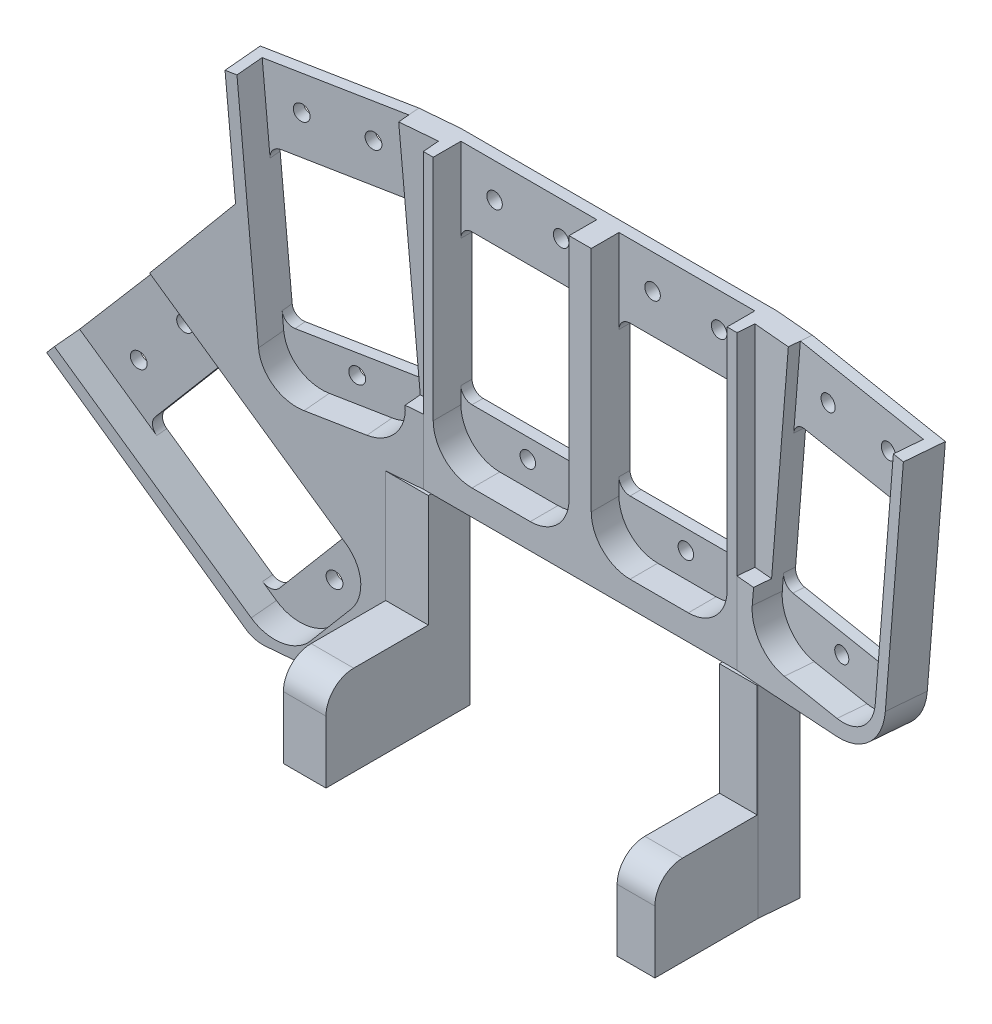
SolidWorks part; units mm, degrees
ref_plane "前视基准面" through (0, 0, 0) normal (0, 0, 1) x (1, 0, 0)
ref_plane "上视基准面" through (0, 0, 0) normal (0, 1, 0) x (1, 0, 0)
ref_plane "右视基准面" through (0, 0, 0) normal (1, 0, 0) x (0, 0, -1)
other "Configuration Table"
sketch "草图1" plane through (0, 0, 0) normal (0, 0, 1) x (1, 0, 0)
  line L0 (-6.3171, -14.436) -> (-6.3171, -11.436)
  line L1 (-8.3171, -13.436) -> (-28.8171, -13.436)
  line L2 (-30.8171, -11.436) -> (-30.8171, -14.436)
  line L3 (-23.8171, -21.436) -> (-13.3171, -21.436)
  line L4 (22.1829, -14.436) -> (22.1829, -11.436)
  line L5 (20.1829, -13.436) -> (-0.3171, -13.436)
  line L6 (-2.3171, -11.436) -> (-2.3171, -14.436)
  line L7 (4.6829, -21.436) -> (15.1829, -21.436)
  line L8 (22.1829, 11.564) -> (22.1829, 26.7199)
  line L9 (22.1829, 26.7199) -> (-2.3171, 26.7199)
  line L10 (-2.3171, 26.7199) -> (-2.3171, 11.564)
  line L11 (-0.3171, 13.564) -> (20.1829, 13.564)
  line L12 (-6.3171, 11.564) -> (-6.3171, 26.7199)
  line L13 (-6.3171, 26.7199) -> (-30.8171, 26.7199)
  line L14 (-30.8171, 26.7199) -> (-30.8171, 11.564)
  line L15 (-28.8171, 13.564) -> (-8.3171, 13.564)
  line L16 (-30.8171, 11.564) -> (-30.8171, -11.436)
  line L17 (-6.3171, 11.564) -> (-6.3171, -11.436)
  line L18 (22.1829, 11.564) -> (22.1829, -11.436)
  line L19 (-2.3171, 11.564) -> (-2.3171, -11.436)
  line L20 (-6.3171, 26.7199) -> (-2.3171, 26.7199)
  line L21 (-30.8171, 26.7199) -> (-32.8171, 26.7199)
  line L22 (-32.8171, 26.7199) -> (-32.8171, -25.4093)
  line L23 (-32.8171, -25.4093) -> (24.1829, -25.4093)
  line L24 (22.1829, 26.7199) -> (24.1829, 26.7199)
  line L25 (24.1829, 26.7199) -> (24.1829, -25.4093)
  arc A0 (-13.3171, -21.436) -> (-6.3171, -14.436) centre (-13.3171, -14.436) ccw
  arc A1 (-8.3171, -13.436) -> (-6.3171, -11.436) centre (-8.3171, -11.436) ccw
  arc A2 (-30.8171, -11.436) -> (-28.8171, -13.436) centre (-28.8171, -11.436) ccw
  arc A3 (-30.8171, -14.436) -> (-23.8171, -21.436) centre (-23.8171, -14.436) ccw
  arc A4 (15.1829, -21.436) -> (22.1829, -14.436) centre (15.1829, -14.436) ccw
  arc A5 (20.1829, -13.436) -> (22.1829, -11.436) centre (20.1829, -11.436) ccw
  arc A6 (-2.3171, -11.436) -> (-0.3171, -13.436) centre (-0.3171, -11.436) ccw
  arc A7 (-2.3171, -14.436) -> (4.6829, -21.436) centre (4.6829, -14.436) ccw
  arc A8 (-0.3171, 13.564) -> (-2.3171, 11.564) centre (-0.3171, 11.564) ccw
  arc A9 (22.1829, 11.564) -> (20.1829, 13.564) centre (20.1829, 11.564) ccw
  arc A10 (-28.8171, 13.564) -> (-30.8171, 11.564) centre (-28.8171, 11.564) ccw
  arc A11 (-6.3171, 11.564) -> (-8.3171, 13.564) centre (-8.3171, 11.564) ccw
sketch "草图2" plane through (0, 0, 0) normal (0, 0, 1) x (1, 0, 0)
  line L0 (-6.3171, -14.436) -> (-6.3171, -11.436)
  line L1 (-8.3171, -13.436) -> (-28.8171, -13.436)
  line L2 (-30.8171, -11.436) -> (-30.8171, -14.436)
  line L3 (-23.8171, -21.436) -> (-13.3171, -21.436)
  line L4 (22.1829, -14.436) -> (22.1829, -11.436)
  line L5 (20.1829, -13.436) -> (-0.3171, -13.436)
  line L6 (-2.3171, -11.436) -> (-2.3171, -14.436)
  line L7 (4.6829, -21.436) -> (15.1829, -21.436)
  line L8 (22.1829, 11.564) -> (22.1829, 26.7199)
  line L9 (22.1829, 26.7199) -> (-2.3171, 26.7199)
  line L10 (-2.3171, 26.7199) -> (-2.3171, 11.564)
  line L11 (-0.3171, 13.564) -> (20.1829, 13.564)
  line L12 (-6.3171, 11.564) -> (-6.3171, 26.7199)
  line L13 (-6.3171, 26.7199) -> (-30.8171, 26.7199)
  line L14 (-30.8171, 26.7199) -> (-30.8171, 11.564)
  line L15 (-28.8171, 13.564) -> (-8.3171, 13.564)
  line L16 (-30.8171, 11.564) -> (-30.8171, -11.436)
  line L17 (-6.3171, 11.564) -> (-6.3171, -11.436)
  line L18 (22.1829, 11.564) -> (22.1829, -11.436)
  line L19 (-2.3171, 11.564) -> (-2.3171, -11.436)
  line L20 (-6.3171, 26.7199) -> (-2.3171, 26.7199)
  line L21 (-30.8171, 26.7199) -> (-32.8171, 26.7199)
  line L22 (-32.8171, 26.7199) -> (-32.8171, -25.4093)
  line L23 (-32.8171, -25.4093) -> (24.1829, -25.4093)
  line L24 (22.1829, 26.7199) -> (24.1829, 26.7199)
  line L25 (24.1829, 26.7199) -> (24.1829, -25.4093)
  arc A0 (-13.3171, -21.436) -> (-6.3171, -14.436) centre (-13.3171, -14.436) ccw
  arc A1 (-8.3171, -13.436) -> (-6.3171, -11.436) centre (-8.3171, -11.436) ccw
  arc A2 (-30.8171, -11.436) -> (-28.8171, -13.436) centre (-28.8171, -11.436) ccw
  arc A3 (-30.8171, -14.436) -> (-23.8171, -21.436) centre (-23.8171, -14.436) ccw
  arc A4 (15.1829, -21.436) -> (22.1829, -14.436) centre (15.1829, -14.436) ccw
  arc A5 (20.1829, -13.436) -> (22.1829, -11.436) centre (20.1829, -11.436) ccw
  arc A6 (-2.3171, -11.436) -> (-0.3171, -13.436) centre (-0.3171, -11.436) ccw
  arc A7 (-2.3171, -14.436) -> (4.6829, -21.436) centre (4.6829, -14.436) ccw
  arc A8 (-0.3171, 13.564) -> (-2.3171, 11.564) centre (-0.3171, 11.564) ccw
  arc A9 (22.1829, 11.564) -> (20.1829, 13.564) centre (20.1829, 11.564) ccw
  arc A10 (-28.8171, 13.564) -> (-30.8171, 11.564) centre (-28.8171, 11.564) ccw
  arc A11 (-6.3171, 11.564) -> (-8.3171, 13.564) centre (-8.3171, 11.564) ccw
extrude "凸台-拉伸3" add sketch "草图1" along normal blind 2 contours A11 L12 L13 L14 A10 L15 | A9 L8 L9 L10 A8 L11 | L6 A7 L7 A4 L4 A5 L5 A6 | L2 A3 L3 A0 L0 A1 L1 A2 | A7 L6 L19 L10 L20 L12 L17 L0 A0 L3 A3 L2 L16 L14 L21 L22 L23 L25 L24 L8 L18 L4 A4 L7
sketch "草图4" plane through (0, 0, 2) normal (0, 0, 1) x (1, 0, 0)
  line L0 (4.6829, -21.436) -> (15.1829, -21.436) construction
  line L1 (22.1829, -14.436) -> (22.1829, -11.436) construction
  line L2 (22.1829, 11.564) -> (22.1829, -11.436) construction
  line L3 (22.1829, 26.7199) -> (24.1829, 26.7199) construction
  line L4 (24.1829, 26.7199) -> (24.1829, -25.4093) construction
  line L5 (22.1829, 11.564) -> (22.1829, 26.7199) construction
  line L6 (-2.3171, 26.7199) -> (-2.3171, 11.564) construction
  line L7 (-2.3171, 11.564) -> (-2.3171, -11.436) construction
  line L8 (-2.3171, -11.436) -> (-2.3171, -14.436) construction
  line L9 (-32.8171, -25.4093) -> (24.1829, -25.4093) construction
  line L10 (-32.8171, 26.7199) -> (-32.8171, -25.4093) construction
  line L11 (-30.8171, 26.7199) -> (-32.8171, 26.7199) construction
  line L12 (-6.3171, 11.564) -> (-6.3171, 26.7199) construction
  line L13 (-6.3171, 11.564) -> (-6.3171, -11.436) construction
  line L14 (-6.3171, -14.436) -> (-6.3171, -11.436) construction
  line L15 (-23.8171, -21.436) -> (-13.3171, -21.436) construction
  line L16 (-30.8171, -11.436) -> (-30.8171, -14.436) construction
  line L17 (-30.8171, 11.564) -> (-30.8171, -11.436) construction
  line L18 (-30.8171, 26.7199) -> (-30.8171, 11.564) construction
  line L19 (4.6829, -21.436) -> (15.1829, -21.436)
  line L20 (22.1829, -14.436) -> (22.1829, -11.436)
  line L21 (22.1829, 11.564) -> (22.1829, -11.436)
  line L22 (22.1829, 26.7199) -> (24.1829, 26.7199)
  line L23 (24.1829, 26.7199) -> (24.1829, -25.4093)
  line L24 (22.1829, 11.564) -> (22.1829, 26.7199)
  line L25 (-2.3171, 26.7199) -> (-2.3171, 11.564)
  line L26 (-2.3171, 11.564) -> (-2.3171, -11.436)
  line L27 (-2.3171, -11.436) -> (-2.3171, -14.436)
  line L28 (-32.8171, -25.4093) -> (24.1829, -25.4093)
  line L29 (-32.8171, 26.7199) -> (-32.8171, -25.4093)
  line L30 (-30.8171, 26.7199) -> (-32.8171, 26.7199)
  line L31 (-6.3171, 11.564) -> (-6.3171, 26.7199)
  line L32 (-6.3171, 11.564) -> (-6.3171, -11.436)
  line L33 (-6.3171, -14.436) -> (-6.3171, -11.436)
  line L34 (-23.8171, -21.436) -> (-13.3171, -21.436)
  line L35 (-30.8171, -11.436) -> (-30.8171, -14.436)
  line L36 (-30.8171, 11.564) -> (-30.8171, -11.436)
  line L37 (-30.8171, 26.7199) -> (-30.8171, 11.564)
  line L38 (-6.3171, 26.7199) -> (-2.3171, 26.7199)
  arc A0 (15.1829, -21.436) -> (22.1829, -14.436) centre (15.1829, -14.436) ccw construction
  arc A1 (-2.3171, -14.436) -> (4.6829, -21.436) centre (4.6829, -14.436) ccw construction
  arc A2 (-13.3171, -21.436) -> (-6.3171, -14.436) centre (-13.3171, -14.436) ccw construction
  arc A3 (-30.8171, -14.436) -> (-23.8171, -21.436) centre (-23.8171, -14.436) ccw construction
  arc A4 (15.1829, -21.436) -> (22.1829, -14.436) centre (15.1829, -14.436) ccw
  arc A5 (-2.3171, -14.436) -> (4.6829, -21.436) centre (4.6829, -14.436) ccw
  arc A6 (-13.3171, -21.436) -> (-6.3171, -14.436) centre (-13.3171, -14.436) ccw
  arc A7 (-30.8171, -14.436) -> (-23.8171, -21.436) centre (-23.8171, -14.436) ccw
extrude "凸台-拉伸4" add sketch "草图4" along normal blind 5
sketch "草图5" plane through (0, 0, 2) normal (0, 0, 1) x (1, 0, 0)
  circle A0 centre (9.747, -16.936) radius 1.4
  circle A5 centre (-18.753, -16.936) radius 1.4
  circle A10 centre (-24.753, 20.564) radius 1.4
  circle A11 centre (-12.753, 20.564) radius 1.4
  circle A13 centre (3.747, 20.564) radius 1.4
  circle A14 centre (15.747, 20.564) radius 1.4
extrude "切除-拉伸1" cut sketch "草图5" against normal blind 5
sketch "草图7" plane through (0, 26.7199, 0) normal (0, 1, 0) x (1, 0, 0)
  line L0 (-32.8171, 0) -> (-70.2267, -3.2729)
  line L1 (-32.8171, -7) -> (-32.8171, 0) construction
  line L2 (-32.8171, 0) -> (-32.8171, -2)
  line L3 (-32.8171, -2) -> (-70.053, -5.2577)
  line L4 (-70.2267, -3.2729) -> (-70.053, -5.2577)
  dimension "D1" = 85
extrude "凸台-拉伸5" add sketch "草图7" against normal up to surface (52.1292 mm away) up to face at (-4.3171, -25.4093, 3.5)
sketch "草图8" plane through (-0.0756, 0, -0.8645) normal (0.0872, 0, 0.9962) x (0.9962, 0, -0.0872)
  line L0 (-36.1156, -14.2794) -> (-36.3771, -11.2908)
  line L2 (-60.7838, -13.4261) -> (-60.5224, -16.4147)
  line L4 (-38.3817, 11.6217) -> (-39.7026, 26.7199)
  line L5 (-39.7026, 26.7199) -> (-64.1093, 24.5846)
  line L6 (-64.1093, 24.5846) -> (-62.7884, 9.4864)
  line L8 (-62.7884, 9.4864) -> (-60.7838, -13.4261)
  line L9 (-38.3817, 11.6217) -> (-36.3771, -11.2908)
  line L10 (-70.2447, 26.7199) -> (-32.8666, 26.7199) construction
  line L11 (-36.1156, -14.2794) -> (-36.3771, -11.2908)
  line L12 (-38.1951, -13.4575) -> (-58.6171, -15.2442)
  line L13 (-52.9389, -22.7779) -> (-42.4789, -21.8628)
  line L14 (-60.9703, 11.6531) -> (-40.5484, 13.4398)
  line L15 (-38.3817, 11.6217) -> (-39.7026, 26.7199)
  arc A1 (-38.1951, -13.4575) -> (-36.3771, -11.2908) centre (-38.3695, -11.4651) ccw
  arc A2 (-60.7838, -13.4261) -> (-58.6171, -15.2442) centre (-58.7915, -13.2518) ccw
  arc A3 (-60.5224, -16.4147) -> (-52.9389, -22.7779) centre (-53.549, -15.8046) ccw
  arc A4 (-60.9703, 11.6531) -> (-62.7884, 9.4864) centre (-60.796, 9.6607) ccw
  arc A5 (-38.3817, 11.6217) -> (-40.5484, 13.4398) centre (-40.374, 11.4474) ccw
  circle A6 centre (-48.2863, -17.8537) radius 1.4
  arc A7 (-38.1951, -13.4575) -> (-36.3771, -11.2908) centre (-38.3695, -11.4651) ccw
  arc A8 (-42.4789, -21.8628) -> (-36.1156, -14.2794) centre (-43.089, -14.8894) ccw
  circle A9 centre (-57.5318, 18.9807) radius 1.4
  circle A10 centre (-45.5775, 20.0265) radius 1.4
  arc A11 (-38.3817, 11.6217) -> (-40.5484, 13.4398) centre (-40.374, 11.4474) ccw
extrude "切除-拉伸2" cut sketch "草图8" against normal blind 54 contours A9 | A10 | A6 | L9 A5 L14 A4 L8 A2 L12 A1
sketch "草图9" plane through (-0.0756, 0, -0.8645) normal (0.0872, 0, 0.9962) x (0.9962, 0, -0.0872)
  line L0 (-38.3817, 11.6217) -> (-39.7026, 26.7199)
  line L1 (-70.2447, 26.7199) -> (-32.8666, 26.7199) construction
  line L2 (-39.7026, 26.7199) -> (-32.8666, 26.7199)
  line L3 (-32.8666, 26.7199) -> (-32.8666, -25.4093)
  line L4 (-32.8666, -25.4093) -> (-61.7354, -25.4093)
  line L5 (-60.7838, -13.4261) -> (-60.5224, -16.4147)
  line L6 (-60.7838, -13.4261) -> (-62.7884, 9.4864)
  line L7 (-62.7884, 9.4864) -> (-64.2962, 26.7199)
  line L8 (-64.2962, 26.7199) -> (-66.2962, 26.7199)
  line L9 (-66.2962, 26.7199) -> (-61.7354, -25.4093)
  line L10 (-60.7838, -13.4261) -> (-60.5224, -16.4147)
  line L11 (-36.1156, -14.2794) -> (-36.3771, -11.2908)
  line L13 (-52.9389, -22.7779) -> (-42.4789, -21.8628)
  line L14 (-38.3817, 11.6217) -> (-36.3771, -11.2908)
  circle A0 centre (-48.2863, -17.8537) radius 1.4
  arc A2 (-60.5224, -16.4147) -> (-52.9389, -22.7779) centre (-53.549, -15.8046) ccw
  arc A4 (-42.4789, -21.8628) -> (-36.1156, -14.2794) centre (-43.089, -14.8894) ccw
  line M17 (-70.2447, -25.4093) -> (-32.8666, -25.4093)
  line M18 (-32.8666, -25.4093) -> (-32.8666, 26.7199)
  line M19 (-32.8666, 26.7199) -> (-70.2447, 26.7199)
  line M22 (-38.3817, 11.6217) -> (-36.3771, -11.2908)
  line M26 (-60.7838, -13.4261) -> (-62.7884, 9.4864)
extrude "凸台-拉伸6" add sketch "草图9" along normal blind 5 contours A4 L13 A2 L5 L7 L9 L0 L11 M26 M19 M17 M18 M22
sketch "草图10" plane through (0, 26.7199, 0) normal (0, 1, 0) x (1, 0, 0)
  line L0 (24.1829, 0) -> (76.1307, -4.5448)
  line L1 (24.1829, -7) -> (24.1829, 0) construction
  line L3 (24.1829, -2) -> (76.1722, -6.5485)
  line L4 (76.1307, -4.5448) -> (76.1722, -6.5485)
  line L5 (24.1829, 0) -> (24.1829, -2)
  dimension "D1" = 85
extrude "凸台-拉伸7" add sketch "草图10" against normal up to surface (52.1292 mm away) up to face at (-35.0058, -25.4093, 4.568)
sketch "草图11" plane through (0.01, 0, -0.1148) normal (-0.0872, 0, 0.9962) x (0.9962, 0, 0.0872)
  line L0 (29.7802, 11.6217) -> (27.7757, -11.2908)
  line L1 (44.3375, -22.7779) -> (33.8775, -21.8628)
  line L2 (27.5142, -14.2794) -> (27.7757, -11.2908)
  line L3 (52.1824, -13.4261) -> (51.921, -16.4147)
  line L4 (57.6948, 26.7199) -> (53.134, -25.4093)
  line L5 (55.6948, 26.7199) -> (57.6948, 26.7199)
  line L6 (54.187, 9.4864) -> (55.6948, 26.7199)
  line L7 (52.1824, -13.4261) -> (54.187, 9.4864)
  line L8 (52.1824, -13.4261) -> (51.921, -16.4147)
  line L9 (24.2652, -25.4093) -> (53.134, -25.4093)
  line L10 (24.2652, 26.7199) -> (24.2652, -25.4093)
  line L11 (31.1012, 26.7199) -> (24.2652, 26.7199)
  line L12 (29.7802, 11.6217) -> (31.1012, 26.7199)
  arc A0 (33.8775, -21.8628) -> (27.5142, -14.2794) centre (34.4876, -14.8894) cw
  arc A1 (51.921, -16.4147) -> (44.3375, -22.7779) centre (44.9476, -15.8046) cw
  circle A2 centre (39.6849, -17.8537) radius 1.4
  line M1 (24.2652, -25.4093) -> (76.4531, -25.4093)
  line M3 (76.4531, 26.7199) -> (24.2652, 26.7199)
  line M4 (24.2652, 26.7199) -> (24.2652, -25.4093)
extrude "凸台-拉伸8" add sketch "草图11" along normal blind 5 contours L3 A1 L1 A0 L2 L0 L12 L4 L6 L7 M3 M4 M1
sketch "草图12" plane through (0.01, 0, -0.1148) normal (-0.0872, 0, 0.9962) x (0.9962, 0, 0.0872)
  line L6 (50.0157, -15.2442) -> (29.5937, -13.4575)
  line L8 (31.9469, 13.4398) -> (52.3689, 11.6531)
  line L9 (29.7802, 11.6217) -> (27.7757, -11.2908)
  line L10 (54.187, 9.4864) -> (52.1824, -13.4261)
  circle A5 centre (36.6057, 20.0589) radius 1.4
  circle A6 centre (48.56, 19.0131) radius 1.4
  circle A7 centre (39.3145, -17.8213) radius 1.4
  arc A8 (27.7757, -11.2908) -> (29.5937, -13.4575) centre (29.768, -11.4651) ccw
  arc A10 (50.0157, -15.2442) -> (52.1824, -13.4261) centre (50.19, -13.2518) ccw
  arc A12 (54.187, 9.4864) -> (52.3689, 11.6531) centre (52.1946, 9.6607) ccw
  arc A13 (31.9469, 13.4398) -> (29.7802, 11.6217) centre (31.7726, 11.4474) ccw
extrude "切除-拉伸3" cut sketch "草图12" against normal blind 5
sketch "草图14" plane through (0, -25.4093, 0) normal (0, -1, 0) x (1, 0, 0)
  line L12 (52.5061, 9.4971) -> (23.9646, 7)
  line L13 (23.9646, 7) -> (-32.5988, 7)
  line L14 (-32.5988, 7) -> (-61.1404, 9.4971)
  line L15 (-61.1404, 9.4971) -> (-61.5762, 4.5161)
  line L16 (-61.5762, 4.5161) -> (-70.053, 5.2577)
  line L17 (-70.053, 5.2577) -> (-70.2267, 3.2729)
  line L18 (-70.2267, 3.2729) -> (-32.8171, 0)
  line L19 (-32.8171, 0) -> (24.1829, 0)
  line L20 (24.1829, 0) -> (76.1307, 4.5448)
  line L21 (76.1307, 4.5448) -> (76.1722, 6.5485)
  line L22 (76.1722, 6.5485) -> (52.9419, 4.5161)
  line L23 (52.9419, 4.5161) -> (52.5061, 9.4971)
  line L24 (52.5061, 9.4971) -> (23.9646, 7)
  line L26 (-32.5988, 7) -> (-61.1404, 9.4971)
  line L27 (-61.1404, 9.4971) -> (-61.5762, 4.5161)
  line L28 (-61.5762, 4.5161) -> (-70.053, 5.2577)
  line L29 (-70.053, 5.2577) -> (-70.2267, 3.2729)
  line L30 (-70.2267, 3.2729) -> (-32.8171, 0)
  line L31 (-32.8171, 0) -> (24.1829, 0)
  line L32 (24.1829, 0) -> (76.1307, 4.5448)
  line L33 (76.1307, 4.5448) -> (76.1722, 6.5485)
  line L34 (76.1722, 6.5485) -> (52.9419, 4.5161)
  line L35 (52.9419, 4.5161) -> (52.5061, 9.4971)
  line L36 (23.9646, 7) -> (-32.5988, 7)
  dimension "D1" = 0
extrude "凸台-拉伸9" add sketch "草图14" along normal blind 48
sketch "草图16" plane through (-69.9774, 0, 6.1222) normal (-0.9962, 0, 0.0872) x (0.0872, 0, 0.9962)
  line L4 (-2.8602, 26.7199) -> (-2.8602, -73.4093)
  line L5 (-2.8602, -73.4093) -> (-0.8678, -73.4093)
  line L6 (-0.8678, -73.4093) -> (-0.8678, 26.7199)
  line L7 (-0.8678, 26.7199) -> (-2.8602, 26.7199)
  line L8 (-2.8602, 26.7199) -> (-2.8602, -73.4093)
  line L9 (-2.8602, -73.4093) -> (-0.8678, -73.4093)
  line L10 (-0.8678, -73.4093) -> (-0.8678, 26.7199)
  line L11 (-0.8678, 26.7199) -> (-2.8602, 26.7199)
  dimension "D1" = 0
extrude "凸台-拉伸10" add sketch "草图16" along normal blind 31
sketch "草图19" plane through (-0.0756, 0, -0.8645) normal (0.0872, 0, 0.9962) x (0.9962, 0, -0.0872)
  line L5 (-66.2962, 26.7199) -> (-101.2447, 26.7199)
  line L6 (-101.2447, 26.7199) -> (-101.2447, -73.4093)
  line L7 (-101.2447, -73.4093) -> (-61.7354, -73.4093)
  line L8 (-61.7354, -73.4093) -> (-61.7354, -25.4093)
  line L9 (-61.7354, -25.4093) -> (-66.2962, 26.7199)
  line L10 (-66.2962, 26.7199) -> (-101.2447, 26.7199)
  line L11 (-101.2447, 26.7199) -> (-101.2447, -73.4093)
  line L12 (-101.2447, -73.4093) -> (-61.7354, -73.4093)
  line L13 (-61.7354, -73.4093) -> (-61.7354, -25.4093)
  line L14 (-61.7354, -25.4093) -> (-66.2962, 26.7199)
  dimension "D1" = 0
extrude "凸台-拉伸12" add sketch "草图19" along normal blind 5 contours L10 L11 L12 L13 L14
sketch "草图20" plane through (0.3601, 0, 4.1165) normal (0.0872, 0, 0.9962) x (0.9962, 0, -0.0872)
  line L0 (-45.9906, -40.369) -> (-48.2888, -38.4406)
  line L1 (-48.0423, -41.2583) -> (-61.2194, -56.9622)
  line L2 (-64.0371, -57.2087) -> (-61.7389, -59.1371)
  line L3 (-51.8771, -58.2743) -> (-45.1278, -50.2308)
  line L4 (-78.6472, -12.9668) -> (-94.4978, -31.6491)
  line L5 (-94.4978, -31.6491) -> (-81.6561, -42.4246)
  line L6 (-81.9026, -39.6069) -> (-68.7255, -23.903)
  line L7 (-65.9078, -23.6565) -> (-78.6472, -12.9668)
  line L8 (-81.6561, -42.4246) -> (-64.0371, -57.2087)
  line L9 (-65.9078, -23.6565) -> (-48.2888, -38.4406)
  arc A0 (-45.1278, -50.2308) -> (-45.9906, -40.369) centre (-50.4902, -45.7313) ccw
  arc A1 (-48.0423, -41.2583) -> (-48.2888, -38.4406) centre (-49.5744, -39.9727) ccw
  arc A2 (-64.0371, -57.2087) -> (-61.2194, -56.9622) centre (-62.7515, -55.6766) ccw
  arc A3 (-61.7389, -59.1371) -> (-51.8771, -58.2743) centre (-57.2394, -53.7747) ccw
  arc A4 (-81.9026, -39.6069) -> (-81.6561, -42.4246) centre (-80.3705, -40.8925) ccw
  arc A5 (-65.9078, -23.6565) -> (-68.7255, -23.903) centre (-67.1934, -25.1886) ccw
  circle A6 centre (-76.9391, -22.8016) radius 1.4
  circle A7 centre (-84.6526, -31.9941) radius 1.4
  circle A8 centre (-52.0692, -51.5024) radius 1.4
extrude "切除-拉伸4" cut sketch "草图20" against normal blind 5 contours L9 A5 L6 A4 L8 A2 L1 A1 | A6 | A7 | A5 L7 L4 L5 A4 L6 A7 A6 | L2 A3 L3 A0 L0 A1 L1 A2 A8 | A8
sketch "草图22" plane through (-0.0756, 0, -0.8645) normal (0.0872, 0, 0.9962) x (0.9962, 0, -0.0872)
  circle A6 centre (-76.9391, -22.8016) radius 1.4
  circle A7 centre (-84.6526, -31.9941) radius 1.4
  circle A8 centre (-52.0692, -51.5024) radius 1.4
extrude "切除-拉伸5" cut sketch "草图22" against normal through all
sketch "草图23" plane through (-0.0756, 0, -0.8645) normal (0.0872, 0, 0.9962) x (0.9962, 0, -0.0872)
  line L1 (-48.0423, -41.2583) -> (-61.2194, -56.9622)
  line L6 (-81.9026, -39.6069) -> (-68.7255, -23.903)
  line L8 (-81.6561, -42.4246) -> (-64.0371, -57.2087)
  line L9 (-65.9078, -23.6565) -> (-48.2888, -38.4406)
  arc A1 (-48.0423, -41.2583) -> (-48.2888, -38.4406) centre (-49.5744, -39.9727) ccw
  arc A2 (-64.0371, -57.2087) -> (-61.2194, -56.9622) centre (-62.7515, -55.6766) ccw
  arc A4 (-81.9026, -39.6069) -> (-81.6561, -42.4246) centre (-80.3705, -40.8925) ccw
  arc A5 (-65.9078, -23.6565) -> (-68.7255, -23.903) centre (-67.1934, -25.1886) ccw
extrude "切除-拉伸6" cut sketch "草图23" against normal through all
sketch "草图24" plane through (0.3601, 0, 4.1165) normal (0.0872, 0, 0.9962) x (0.9962, 0, -0.0872)
  line L0 (-78.6472, -12.9668) -> (-94.4978, -31.6491)
  line L1 (-48.3684, -73.4093) -> (-101.2447, -73.4093)
  line L6 (-64.2962, 26.7199) -> (-101.2447, 26.7199) construction
  line L7 (-66.2962, 26.7199) -> (-64.3389, 4.3484)
  line L8 (-78.6472, -12.9668) -> (-64.3389, 4.3484)
  line L9 (-66.2962, 26.7199) -> (-101.2447, 26.7199)
  line L10 (-101.2447, 26.7199) -> (-101.2447, -73.4093)
  line L11 (-94.4978, -31.6491) -> (-95.7917, -33.1742)
  line L12 (-95.7917, -33.1742) -> (-48.3684, -73.4093)
  line L13 (-33.0849, -73.4093) -> (-101.2447, -73.4093) construction
extrude "切除-拉伸7" cut sketch "草图24" against normal through all
sketch "草图25" plane through (0, 0, 7) normal (0, 0, 1) x (1, 0, 0)
  line L8 (28.1628, -26.0179) -> (21.3541, -26.0179)
  line L9 (21.3541, -26.0179) -> (21.3541, -62.4789)
  line L10 (21.3541, -62.4789) -> (28.1628, -62.4789)
  line L11 (28.1628, -62.4789) -> (28.1628, -26.0179)
  line L12 (-38.8372, -62.4789) -> (-31.1575, -62.4789)
  line L13 (-31.1575, -62.4789) -> (-31.1575, -26.0179)
  line L14 (-31.1575, -26.0179) -> (-38.8372, -26.0179)
  line L15 (-38.8372, -26.0179) -> (-38.8372, -62.4789)
extrude "凸台-拉伸14" add sketch "草图25" along normal blind 19
sketch "草图26" plane through (0, 0, 7) normal (0, 0, 1) x (1, 0, 0)
  line L1 (-38.8372, -62.4789) -> (76.1722, -62.4789)
  line L2 (-38.8372, -62.4789) -> (-38.8372, -73.4093)
  line L3 (-38.8372, -73.4093) -> (76.1722, -73.4093)
  line L4 (76.1722, -62.4789) -> (76.1722, -73.4093)
  line L5 (-38.8372, -62.4789) -> (-63.6236, -62.4789)
  line L6 (-38.8372, -62.4789) -> (-38.8372, -73.4093)
  line L7 (-38.8372, -73.4093) -> (-63.6236, -73.4093)
  line L8 (-63.6236, -62.4789) -> (-63.6236, -73.4093)
  line M24 (-31.1575, -62.4789) -> (-32.5988, -62.4789)
  line M25 (-32.5988, -62.4789) -> (-32.5988, -73.4093)
  line M26 (-32.5988, -73.4093) -> (23.9646, -73.4093)
  line M27 (23.9646, -73.4093) -> (23.9646, -62.4789)
  line M28 (23.9646, -62.4789) -> (21.3541, -62.4789)
extrude "切除-拉伸8" cut sketch "草图26" against normal through all and the other way through all contours L5 L8 L7 L2 | L1 M24 M25 M26 M27 M28 | L4 L1 L3 M27 | L2 L3 L1 M25
sketch "草图27" plane through (-0.4257, 0, 4.8661) normal (-0.0872, 0, 0.9962) x (0.9962, 0, 0.0872)
  line L1 (57.6948, 26.7199) -> (53.134, -25.4093) construction
  line L2 (57.6948, 26.7199) -> (53.134, -25.4093) construction
  line L3 (53.134, -25.4093) -> (28.6978, -26.0179)
  line L4 (28.6978, -26.0179) -> (28.6978, -62.4789)
  line L5 (28.6978, -62.4789) -> (53.134, -62.4789)
  line L7 (53.134, -62.4789) -> (53.134, -25.4093)
extrude "切除-拉伸9" cut sketch "草图27" against normal through all contours L3 L4 L5 L7
sketch "草图28" plane through (0.01, 0, -0.1148) normal (-0.0872, 0, 0.9962) x (0.9962, 0, 0.0872)
  line L5 (53.134, -62.4789) -> (76.4531, -62.4789)
  line L6 (76.4531, -62.4789) -> (76.4531, 26.7199)
  line L7 (76.4531, 26.7199) -> (57.6948, 26.7199)
  line L8 (57.6948, 26.7199) -> (53.134, -25.4093)
  line L11 (76.4531, -62.4789) -> (76.4531, 26.7199)
  line L12 (76.4531, 26.7199) -> (57.6948, 26.7199)
  line L13 (57.6948, 26.7199) -> (53.134, -25.4093)
  line L15 (53.134, -62.4789) -> (76.4531, -62.4789)
  line L17 (53.134, -25.4093) -> (53.134, -62.4789)
  line L18 (53.134, -25.4093) -> (53.134, -62.4789)
  dimension "D1" = 0
extrude "切除-拉伸10" cut sketch "草图28" against normal through all
sketch "草图29" plane through (-0.0756, 0, -0.8645) normal (0.0872, 0, 0.9962) x (0.9962, 0, -0.0872)
  line L0 (-39.7026, 26.7199) -> (-66.0942, 24.411)
  line L1 (-64.3389, 4.3484) -> (-66.2962, 26.7199) construction
  line L2 (-66.0942, 24.411) -> (-66.2962, 26.7199)
  line L3 (-66.2962, 26.7199) -> (-39.7026, 26.7199)
extrude "切除-拉伸11" cut sketch "草图29" against normal through all and the other way through all
sketch "草图31" plane through (0.01, 0, -0.1148) normal (-0.0872, 0, 0.9962) x (0.9962, 0, 0.0872)
  line L0 (31.1012, 26.7199) -> (57.4927, 24.411)
  line L1 (57.6948, 26.7199) -> (53.134, -25.4093) construction
  line L2 (57.4927, 24.411) -> (57.6948, 26.7199)
  line L3 (57.6948, 26.7199) -> (31.1012, 26.7199)
extrude "切除-拉伸13" cut sketch "草图31" against normal through all and the other way through all
sketch "草图32" plane through (0.3601, 0, 4.1165) normal (0.0872, 0, 0.9962) x (0.9962, 0, -0.0872)
  line L14 (-61.2515, -62.4789) -> (-39.347, -62.4789)
  line L15 (-39.347, -62.4789) -> (-39.347, -26.0179)
  line L16 (-64.1093, 24.5846) -> (-66.0942, 24.411)
  line L17 (-66.0942, 24.411) -> (-64.3389, 4.3484)
  line L18 (-64.3389, 4.3484) -> (-78.6472, -12.9668)
  line L19 (-78.6472, -12.9668) -> (-45.9906, -40.369)
  line L20 (-45.1278, -50.2308) -> (-51.8771, -58.2743)
  line L21 (-61.7389, -59.1371) -> (-94.4978, -31.6491)
  line L22 (-94.4978, -31.6491) -> (-95.7917, -33.1742)
  line L23 (-95.7917, -33.1742) -> (-61.2515, -62.4789)
  line L26 (-39.347, -62.4789) -> (-39.347, -26.0179)
  line L28 (-33.0849, 26.7199) -> (-39.7026, 26.7199)
  line L29 (-39.7026, 26.7199) -> (-36.1156, -14.2794)
  line L30 (-42.4789, -21.8628) -> (-52.9389, -22.7779)
  line L31 (-60.5224, -16.4147) -> (-64.1093, 24.5846)
  line L45 (-39.347, -26.0179) -> (-33.0849, -26.0179)
  line L46 (-33.0849, -26.0179) -> (-33.0849, 26.7199)
  arc A4 (-45.1278, -50.2308) -> (-45.9906, -40.369) centre (-50.4902, -45.7313) ccw
  arc A5 (-61.7389, -59.1371) -> (-51.8771, -58.2743) centre (-57.2394, -53.7747) ccw
  arc A6 (-42.4789, -21.8628) -> (-36.1156, -14.2794) centre (-43.089, -14.8894) ccw
  arc A7 (-60.5224, -16.4147) -> (-52.9389, -22.7779) centre (-53.549, -15.8046) ccw
  dimension "D1" = 0
sketch "草图33" plane through (0.3601, 0, 4.1165) normal (0.0872, 0, 0.9962) x (0.9962, 0, -0.0872)
  line L0 (-39.7026, 26.7199) -> (-33.0849, 26.7199)
  line L1 (-36.1156, -14.2794) -> (-33.0849, -14.2794)
  line L2 (-33.0849, 26.7199) -> (-33.0849, -14.2794)
  line L3 (-33.0849, -26.0179) -> (-33.0849, 26.7199) construction
  line L4 (-36.1156, -14.2794) -> (-39.7026, 26.7199)
extrude "切除-拉伸15" cut sketch "草图33" against normal blind 3
sketch "草图34" plane through (-0.4257, 0, 4.8661) normal (-0.0872, 0, 0.9962) x (0.9962, 0, 0.0872)
  line L0 (31.1012, 26.7199) -> (27.7757, -11.2908)
  line L1 (27.7757, -11.2908) -> (24.4835, -11.2908)
  line L2 (24.4835, 26.7199) -> (24.4835, -26.0179) construction
  line L3 (24.4835, -11.2908) -> (24.4835, 26.7199)
  line L4 (24.4835, 26.7199) -> (31.1012, 26.7199)
extrude "切除-拉伸16" cut sketch "草图34" against normal blind 3
sketch "草图35" plane through (0, 0, 7) normal (0, 0, 1) x (1, 0, 0)
  line L1 (-31.1575, -26.0179) -> (21.3541, -26.0179)
  line L2 (-31.1575, -26.0179) -> (-31.1575, -62.4789)
  line L3 (-31.1575, -62.4789) -> (21.3541, -62.4789)
  line L4 (21.3541, -26.0179) -> (21.3541, -62.4789)
extrude "切除-拉伸18" cut sketch "草图35" against normal blind 11
sketch "草图36" plane through (0, -62.4789, 0) normal (0, -1, 0) x (1, 0, 0)
  circle A0 centre (25.0484, 3) radius 1.4
  circle A1 centre (25.0484, 21) radius 1.4
  circle A2 centre (-35.9516, 3) radius 1.4
  circle A3 centre (-35.9516, 21) radius 1.4
extrude "切除-拉伸19" cut sketch "草图36" against normal blind 5
fillet "圆角1" radius 10 1 edges at (52.8108, -25.4093, 6.0142)
sketch "草图37" plane through (-38.8372, 0, 0) normal (-1, 0, 0) x (0, 0, 1)
  line L0 (7.5458, -62.4789) -> (7.5458, -26.0179) construction
  line L1 (26, -26.0179) -> (7.5458, -26.0179)
  line L2 (26, -26.0179) -> (26, -46.246)
  line L3 (26, -46.246) -> (7.5458, -46.246)
  line L4 (7.5458, -26.0179) -> (7.5458, -46.246)
extrude "切除-拉伸20" cut sketch "草图37" against normal blind 67
fillet "圆角2" radius 5 3 edges at (-60.963, -62.4789, 5.972) (24.7585, -46.246, 26) (-34.9973, -46.246, 26)
